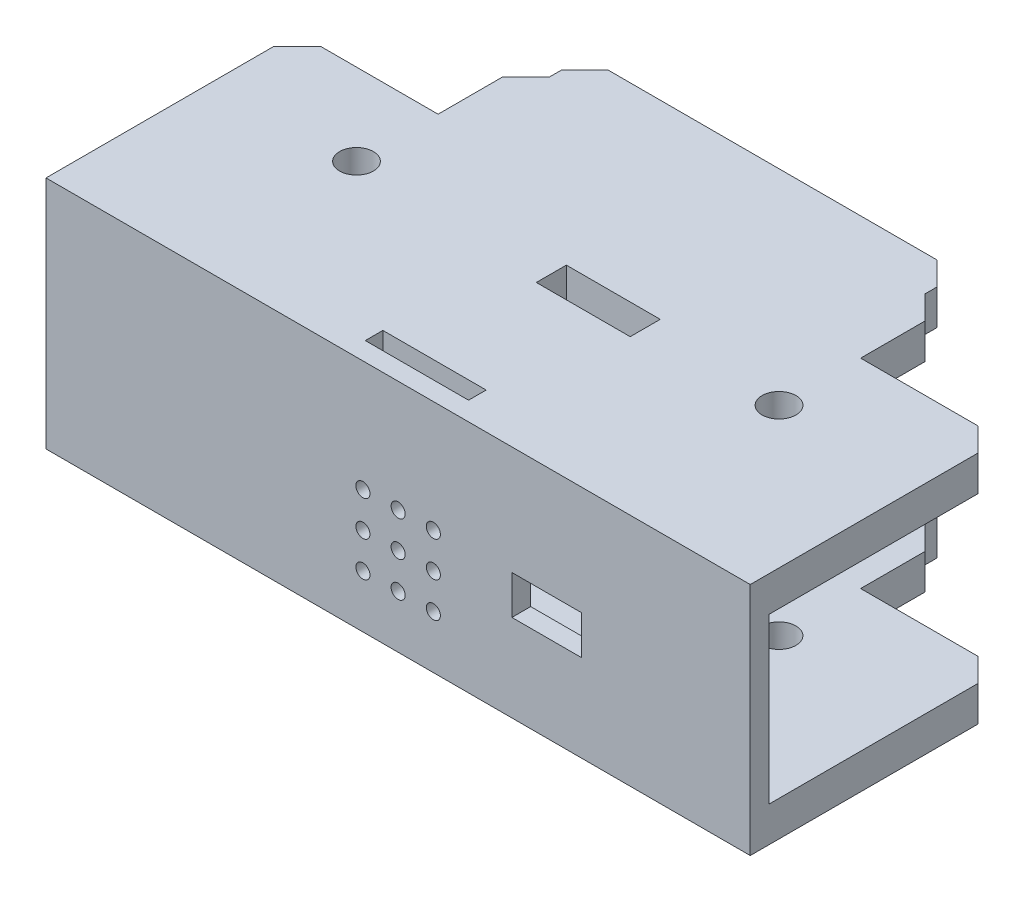
SolidWorks part; units mm, degrees
ref_plane "Front Plane" through (0, 0, 0) normal (0, 0, 1) x (1, 0, 0)
ref_plane "Top Plane" through (0, 0, 0) normal (0, 1, 0) x (1, 0, 0)
ref_plane "Right Plane" through (0, 0, 0) normal (1, 0, 0) x (0, 0, -1)
sketch "Sketch1" plane through (0, 0, 0) normal (0, 1, 0) x (1, 0, 0)
  line L1 (-75, 36.13) -> (75, 36.13)
  line L2 (-75, 36.13) -> (-75, -36.13)
  line L3 (-75, -36.13) -> (75, -36.13)
  line L4 (75, 36.13) -> (75, -36.13)
  line L5 (-75, 36.13) -> (75, -36.13) construction
  line L6 (-75, -36.13) -> (75, 36.13) construction
  point P0 (0, 0)
  dimension "D1" = 72.26
  dimension "D2" = 150
extrude "Boss-Extrude1" add sketch "Sketch1" along normal blind 50
sketch "Sketch2" plane through (0, 50, 0) normal (0, 1, 0) x (1, 0, 0)
  line L0 (-75, 0) -> (75, 0) construction
  line L1 (-75, 36.13) -> (-75, -36.13) construction
  line L2 (75, -36.13) -> (75, 36.13) construction
  circle A0 centre (-45, 0) radius 3.6
  circle A1 centre (45, 0) radius 3.6
  dimension "D1" = 30
  dimension "D2" = 30
extrude "Cut-Extrude1" cut sketch "Sketch2" against normal blind 50
sketch "Sketch3" plane through (0, 0, -36.13) normal (0, 0, -1) x (-1, 0, 0)
  line L0 (-75, 0) -> (75, 0) construction
  line L1 (75, 50) -> (45, 50)
  line L2 (75, 50) -> (75, 0)
  line L3 (75, 0) -> (45, 0)
  line L4 (45, 50) -> (45, 0)
  line L6 (-75, 50) -> (-45, 50)
  line L7 (-75, 50) -> (-75, 0)
  line L8 (-75, 0) -> (-45, 0)
  line L9 (-45, 50) -> (-45, 0)
  dimension "D1" = 30
  dimension "D2" = 30
extrude "Cut-Extrude2" cut sketch "Sketch3" against normal blind 18.75
chamfer "Chamfer1" distance 5 angle 45 4 edges at (75, 25, -17.38) (45, 25, -36.13) (-45, 25, -36.13) (-75, 25, -17.38)
sketch "Sketch4" plane through (0, 0, -36.13) normal (0, 0, -1) x (-1, 0, 0)
  line L0 (40, 0) -> (40, 50) construction
  line L1 (-40, 50) -> (40, 50)
  line L2 (-40, 50) -> (-40, 42.5)
  line L3 (-40, 42.5) -> (40, 42.5)
  line L4 (40, 50) -> (40, 42.5)
  dimension "D1" = 7.5
extrude "Boss-Extrude2" add sketch "Sketch4" along normal blind 7.5
chamfer "Chamfer2" distance 5 angle 45 2 edges at (-40, 46.25, -43.63) (40, 46.25, -43.63)
sketch "Sketch5" plane through (0, 0, -36.13) normal (0, 0, -1) x (-1, 0, 0)
  line L0 (0, 42.5) -> (-75, 42.5) construction
  line L1 (-40, 42.5) -> (40, 42.5) construction
  line L2 (0, 42.5) -> (75, 42.5) construction
  line L3 (0, 7.5) -> (75, 7.5) construction
  line L4 (-40, 0) -> (40, 0) construction
  line L6 (-75, 42.5) -> (75, 42.5)
  line L7 (-75, 42.5) -> (-75, 7.5)
  line L8 (-75, 7.5) -> (75, 7.5)
  line L9 (75, 42.5) -> (75, 7.5)
  dimension "D1" = 75
  dimension "D2" = 75
  dimension "D3" = 75
  dimension "D4" = 7.5
extrude "Cut-Extrude3" cut sketch "Sketch5" against normal blind 68.26
sketch "Sketch10" plane through (0, 0, 36.13) normal (0, 0, 1) x (1, 0, 0)
  line L0 (-75, 7.5) -> (75, 7.5) construction
  line L1 (-75, 50) -> (-75, 0) construction
  line L2 (75, 50) -> (75, 0) construction
  line L3 (-75, 0) -> (75, 0) construction
  line L4 (0, 30) -> (0, 41.3485) construction
  line L5 (-75, 30) -> (75, 30) construction
  line L6 (-3.75, 7.5) -> (-3.75, 30) construction
  line L7 (3.75, 30) -> (3.75, 7.5) construction
  line L8 (-11.25, 30) -> (-11.25, 7.5) construction
  line L9 (11.25, 30) -> (11.25, 7.5) construction
  line L10 (-11.25, 22.5) -> (-3.75, 22.5) construction
  line L11 (-3.75, 22.5) -> (3.75, 22.5) construction
  line L12 (3.75, 22.5) -> (11.25, 22.5) construction
  line L13 (-11.25, 15) -> (-3.75, 15) construction
  line L14 (-3.75, 15) -> (3.75, 15) construction
  line L15 (3.75, 15) -> (11.25, 15) construction
  line L16 (0, 30) -> (0, 22.5) construction
  line L17 (0, 22.5) -> (0, 15) construction
  line L18 (0, 7.5) -> (0, 15) construction
  line L19 (-7.5, 22.5) -> (-7.5, 30) construction
  line L20 (-7.5, 22.5) -> (-7.5, 15) construction
  line L21 (-7.5, 15) -> (-7.5, 7.5) construction
  line L22 (7.5, 22.5) -> (7.5, 30) construction
  line L23 (7.5, 22.5) -> (7.5, 15) construction
  line L24 (7.5, 15) -> (7.5, 7.5) construction
  circle A0 centre (0, 26.25) radius 1.5
  circle A1 centre (0, 18.75) radius 1.5
  circle A2 centre (0, 11.25) radius 1.5
  circle A3 centre (-7.5, 26.25) radius 1.5
  circle A4 centre (-7.5, 18.75) radius 1.5
  circle A5 centre (-7.5, 11.25) radius 1.5
  circle A6 centre (7.5, 26.25) radius 1.5
  circle A7 centre (7.5, 18.75) radius 1.5
  circle A8 centre (7.5, 11.25) radius 1.5
  dimension "D1" = 7.5
  dimension "D2" = 3.75
  dimension "D3" = 22.5
  dimension "D4" = 3.75
  dimension "D5" = 7.5
  dimension "D6" = 7.5
  dimension "D7" = 7.5
  dimension "D8" = 7.5
extrude "Cut-Extrude4" cut sketch "Sketch10" against normal blind 4
sketch "Sketch11" plane through (0, 50, 0) normal (0, 1, 0) x (1, 0, 0)
  line L0 (-75, -32.13) -> (75, -32.13) construction
  line L1 (-75, 12.38) -> (-75, -36.13) construction
  line L2 (75, -36.13) -> (75, 12.38) construction
  line L3 (-75, -36.13) -> (75, -36.13) construction
  line L4 (0, -32.13) -> (0, -28.38) construction
  line L5 (-11, -32.13) -> (-11, -28.38) construction
  line L7 (-11, -28.38) -> (11, -28.38)
  line L8 (-11, -28.38) -> (-11, -32.13)
  line L9 (-11, -32.13) -> (11, -32.13)
  line L10 (11, -28.38) -> (11, -32.13)
  dimension "D1" = 4
  dimension "D2" = 3.75
  dimension "D3" = 11
  dimension "D4" = 22
extrude "Cut-Extrude5" cut sketch "Sketch11" against normal blind 50
sketch "Sketch13" plane through (0, 0, -36.13) normal (0, 0, -1) x (-1, 0, 0)
  line L1 (-40, 7.5) -> (40, 7.5)
  line L2 (-40, 7.5) -> (-40, 0)
  line L3 (-40, 0) -> (40, 0)
  line L4 (40, 7.5) -> (40, 0)
extrude "Boss-Extrude3" add sketch "Sketch13" along normal blind 7.5
sketch "Sketch14" plane through (0, 0, -43.63) normal (0, 0, -1) x (-1, 0, 0)
  line L0 (-40, 3.75) -> (40, 3.75) construction
  line L1 (-40, 7.5) -> (-40, 0) construction
  line L2 (40, 0) -> (40, 7.5) construction
  line L3 (-15, 7.5) -> (-15, 0) construction
  line L4 (40, 7.5) -> (-40, 7.5) construction
  line L5 (-40, 0) -> (40, 0) construction
  line L6 (15, 7.5) -> (15, 0) construction
  circle A0 centre (-15, 3.75) radius 1.5
  circle A1 centre (15, 3.75) radius 1.5
  point P12 (0, 0)
  dimension "D2" = 15
  dimension "D1" = 15
extrude "Cut-Extrude6" cut sketch "Sketch14" against normal blind 7.5
chamfer "Chamfer3" distance 5 angle 45 2 edges at (-40, 3.75, -43.63) (40, 3.75, -43.63)
sketch "Sketch19" plane through (0, 50, 0) normal (0, 1, 0) x (1, 0, 0)
  line L0 (38.5, 0) -> (-35.0956, 0) construction
  line L1 (38.5, 3.2) -> (-1.5, 3.2) construction
  line L2 (-1.5, -3.2) -> (18.3, -3.2) construction
  line L3 (16.5, 3.2) -> (16.5, -3.2) construction
  line L9 (16.5, 3.2) -> (-3.5, 3.2)
  line L10 (16.5, 3.2) -> (16.5, -3.2)
  line L11 (16.5, -3.2) -> (-3.5, -3.2)
  line L12 (-3.5, 3.2) -> (-3.5, -3.2)
  circle A0 centre (45, 0) radius 3.6 construction
  dimension "D1" = 6.5
  dimension "D2" = 40
  dimension "D3" = 0
  dimension "D4" = 22
  dimension "D5" = 3.2
  dimension "D6" = 3.2
  dimension "D7" = 20
extrude "Cut-Extrude10" cut sketch "Sketch19" against normal blind 10
sketch "Sketch20" plane through (0, 0, 36.13) normal (0, 0, 1) x (1, 0, 0)
  line L1 (24.2305, 26.8332) -> (39.0557, 26.8332)
  line L2 (24.2305, 26.8332) -> (24.2305, 18.5439)
  line L3 (24.2305, 18.5439) -> (39.0557, 18.5439)
  line L4 (39.0557, 26.8332) -> (39.0557, 18.5439)
extrude "Cut-Extrude11" cut sketch "Sketch20" against normal blind 9
sketch "Sketch21" plane through (0, 0, 0) normal (0, -1, 0) x (1, 0, 0)
  line L0 (-38.5, 0) -> (24.5697, 0) construction
  line L1 (-16.5, 3.2) -> (3.5, 3.2) construction
  line L2 (-16.5, -3.2) -> (3.5, -3.2) construction
  line L4 (-16.5, 3.2) -> (3.5, 3.2)
  line L5 (-16.5, 3.2) -> (-16.5, -3.2)
  line L6 (-16.5, -3.2) -> (3.5, -3.2)
  line L7 (3.5, 3.2) -> (3.5, -3.2)
  circle A0 centre (-45, 0) radius 3.6 construction
  dimension "D1" = 6.5
  dimension "D2" = 22
  dimension "D3" = 3.2
  dimension "D4" = 20
  dimension "D5" = 3.2
extrude "Cut-Extrude12" cut sketch "Sketch21" against normal blind 10
